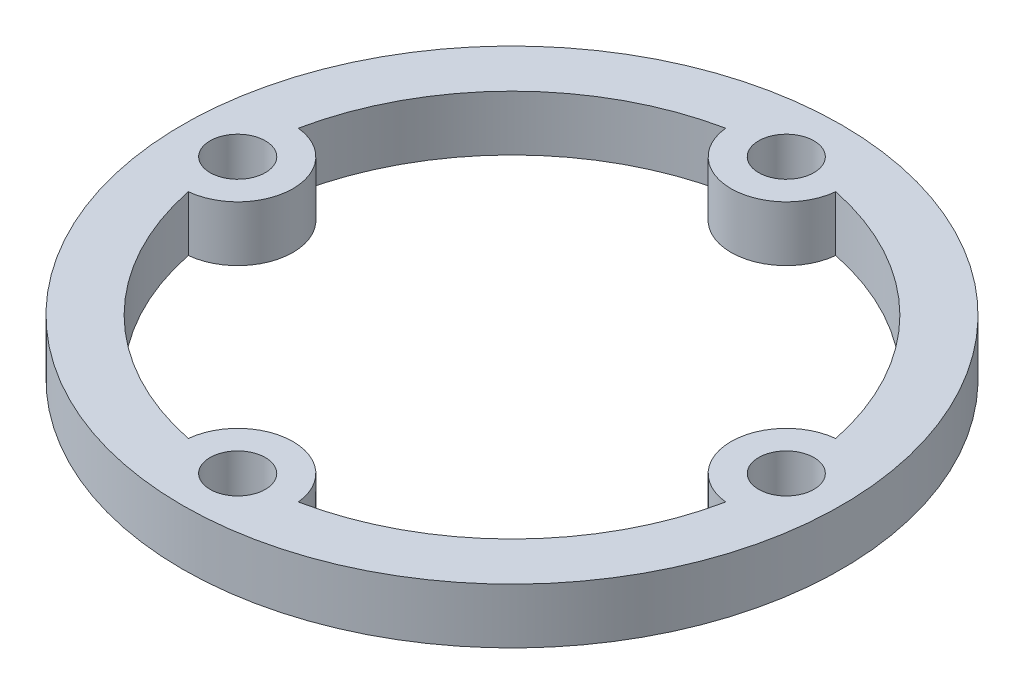
SolidWorks part; units mm, degrees
ref_plane "Front Plane" through (0, 0, 0) normal (0, 0, 1) x (1, 0, 0)
ref_plane "Top Plane" through (0, 0, 0) normal (0, 1, 0) x (1, 0, 0)
ref_plane "Right Plane" through (0, 0, 0) normal (1, 0, 0) x (0, 0, -1)
sketch "Sketch1" plane through (0, 0, 0) normal (0, 1, 0) x (1, 0, 0)
  circle A0 centre (0, 0) radius 11.925
  circle A1 centre (0, 0) radius 9.925
  circle A2 centre (0, 9.925) radius 2
  circle A3 centre (0, 9.925) radius 1
  circle A4 centre (9.925, 0) radius 1
  circle A5 centre (9.925, 0) radius 2
  circle A6 centre (0, 0) radius 9.925
  circle A7 centre (0, -9.925) radius 1
  circle A8 centre (0, -9.925) radius 2
  circle A9 centre (0, 0) radius 9.925
  circle A10 centre (-9.925, 0) radius 1
  circle A11 centre (-9.925, 0) radius 2
  circle A12 centre (0, 0) radius 9.925
  point P21 (0, 0)
  dimension "D1" = 23.85
  dimension "D3" = 2
  dimension "D2" = 2
  dimension "D4" = 4
extrude "Boss-Extrude1" add sketch "Sketch1" along normal blind 2 contours A11 A0 A8 A9 | A9 A11 A1 A10 | A1 A11 A9 A10 | A11 A1 A2 A0 | A3 A1 A2 | A3 A1 A2 | A5 A0 A2 A1 | A1 A5 A4 | A5 A1 A4 | A8 A0 A5 A6 | A8 A1 A7 A6 | A1 A8 A6 A7
equation "\"D1@Sketch1\"=24-0.15"
